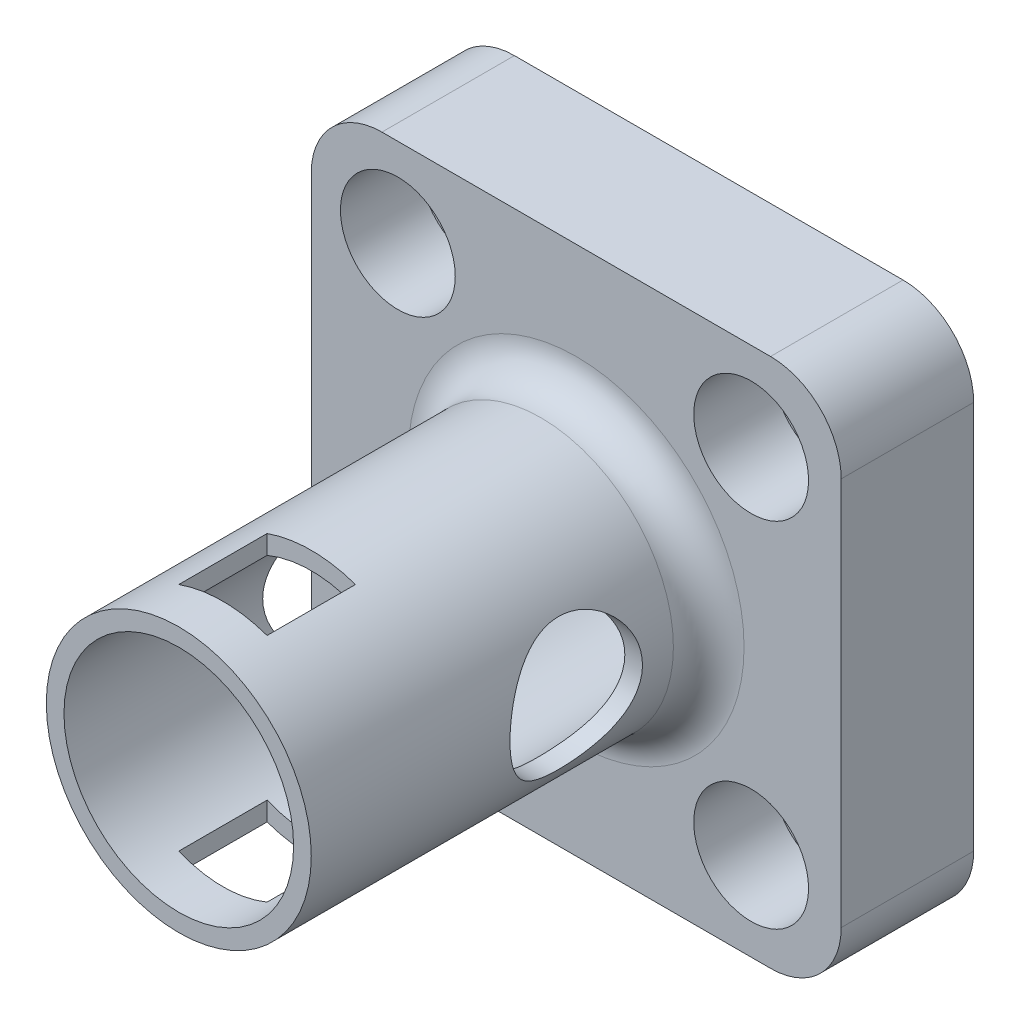
SolidWorks part; units mm, degrees
material "AISI 1010 Aço, barra laminada a quente"
ref_plane "Plano frontal" through (0, 0, 0) normal (0, 0, 1) x (1, 0, 0)
ref_plane "Plano superior" through (0, 0, 0) normal (0, 1, 0) x (1, 0, 0)
ref_plane "Plano direito" through (0, 0, 0) normal (1, 0, 0) x (0, 0, -1)
sketch "Esboço1" plane through (0, 0, 0) normal (0, 1, 0) x (1, 0, 0)
  line L0 (0, 0) -> (0, -15)
  line L1 (0, -15) -> (60, -15)
  line L2 (60, -15) -> (60, 0)
  line L3 (0, 0) -> (60, 0)
  dimension "D1" = 15
  dimension "D2" = 60
extrude "Ressalto-extrusão1" add sketch "Esboço1" along normal blind 60
sketch "Esboço4" plane through (0, 0, 15) normal (0, 0, 1) x (1, 0, 0)
  line L0 (0, 60) -> (60, 60) construction
  circle A0 centre (9.8023, 50) radius 6.5
  circle A1 centre (49.8023, 50) radius 6.5
  circle A2 centre (9.8023, 10) radius 6.5
  circle A3 centre (49.8023, 10) radius 6.5
  dimension "D1" = 13
  dimension "D2" = 13
  dimension "D3" = 13
  dimension "D4" = 13
  dimension "D5" = 40
  dimension "D6" = 40
  dimension "D7" = 40
  dimension "D8" = 10
  dimension "D9" = 10
extrude "Corte-extrusão1" cut sketch "Esboço4" against normal blind 9
sketch "Esboço5" plane through (0, 0, 0) normal (0, 0, -1) x (-1, 0, 0)
  line L1 (-60, 0) -> (0, 0) construction
  line L2 (-60, 60) -> (-60, 0) construction
  circle A0 centre (-50, 50) radius 4.5
  circle A1 centre (-10, 50) radius 4.5
  circle A2 centre (-50, 10) radius 4.5
  circle A5 centre (-10, 10) radius 4.5
  dimension "D1" = 9
  dimension "D2" = 9
  dimension "D3" = 9
  dimension "D4" = 9
  dimension "D5" = 40
  dimension "D6" = 40
  dimension "D7" = 40
  dimension "D8" = 10
  dimension "D9" = 10
  dimension "D10" = 10
extrude "Corte-extrusão2" cut sketch "Esboço5" against normal blind 6
sketch "Esboço6" plane through (0, 0, 15) normal (0, 0, 1) x (1, 0, 0)
  line L0 (0, 60) -> (60, 60) construction
  circle A1 centre (30, 30) radius 15
  point P4 (30, 60)
  dimension "D1" = 30
  dimension "D2" = 30
extrude "Ressalto-extrusão3" add sketch "Esboço6" along normal blind 45
sketch "Esboço7" plane through (0, 0, 60) normal (0, 0, 1) x (1, 0, 0)
  circle A0 centre (30, 30) radius 13
  dimension "D1" = 26
extrude "Corte-extrusão3" cut sketch "Esboço7" against normal through all
fillet "Filete2" radius 4 1 edges at (45, 30, 15)
sketch "Esboço8" plane through (0, 0, 0) normal (1, 0, 0) x (0, 0, -1)
  line L0 (0, 60) -> (0, 0) construction
  circle A0 centre (-30, 30) radius 7.5
  dimension "D1" = 15
  dimension "D2" = 30
extrude "Corte-extrusão10" cut sketch "Esboço8" along normal through all contours A0
sketch "Esboço9" plane through (0, 0, 0) normal (0, 1, 0) x (1, 0, 0)
  line L0 (25, -45) -> (25, -55)
  line L1 (25, -55) -> (35, -55)
  line L2 (35, -55) -> (35, -45)
  line L3 (35, -45) -> (25, -45)
  line L4 (60, 0) -> (0, 0) construction
  line L5 (15, -37.5) -> (15, -60) construction
  point P2 (25, -50)
  point P5 (35, -50)
  dimension "D1" = 10
  dimension "D2" = 10
  dimension "D3" = 50
  dimension "D4" = 10
extrude "Corte-extrusão11" cut sketch "Esboço9" along normal through all
fillet "Filete3" radius 8 4 edges at (60, 60, 7.5) (60, 0, 7.5) (0, 0, 7.5) (0, 60, 7.5)
